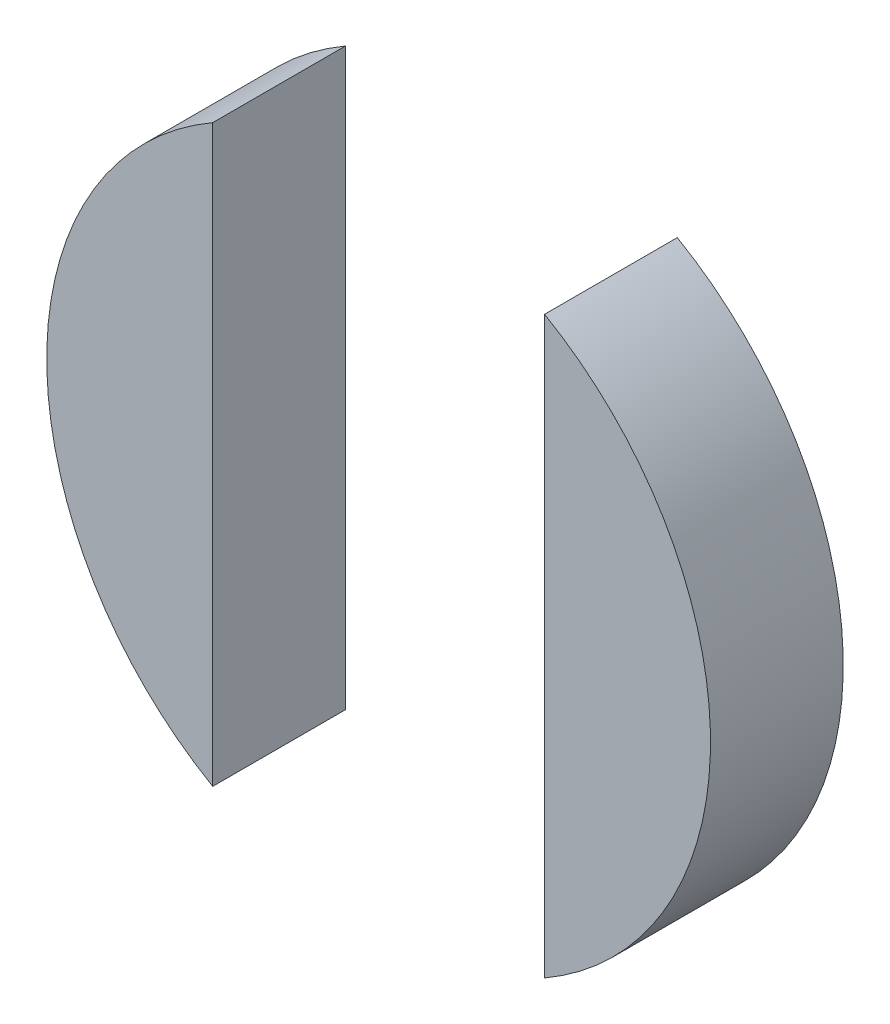
SolidWorks part; units mm, degrees
ref_plane "Front Plane" through (0, 0, 0) normal (0, 0, 1) x (1, 0, 0)
ref_plane "Top Plane" through (0, 0, 0) normal (0, 1, 0) x (1, 0, 0)
ref_plane "Right Plane" through (0, 0, 0) normal (1, 0, 0) x (0, 0, -1)
sketch "Sketch1" plane through (0, 0, 0) normal (0, 0, 1) x (1, 0, 0)
  line L0 (-5, 8.6603) -> (-5, -8.6603)
  line L1 (5, 8.6603) -> (5, -8.6603)
  circle A0 centre (0, 0) radius 10 construction
  arc A2 (-5, 8.6603) -> (-5, -8.6603) centre (0, 0) ccw
  arc A3 (5, 8.6603) -> (5, -8.6603) centre (0, 0) cw
  dimension "D1" = 20
  dimension "D3" = 5
  dimension "D4" = 5
extrude "Boss-Extrude1" add sketch "Sketch1" along normal blind 4
